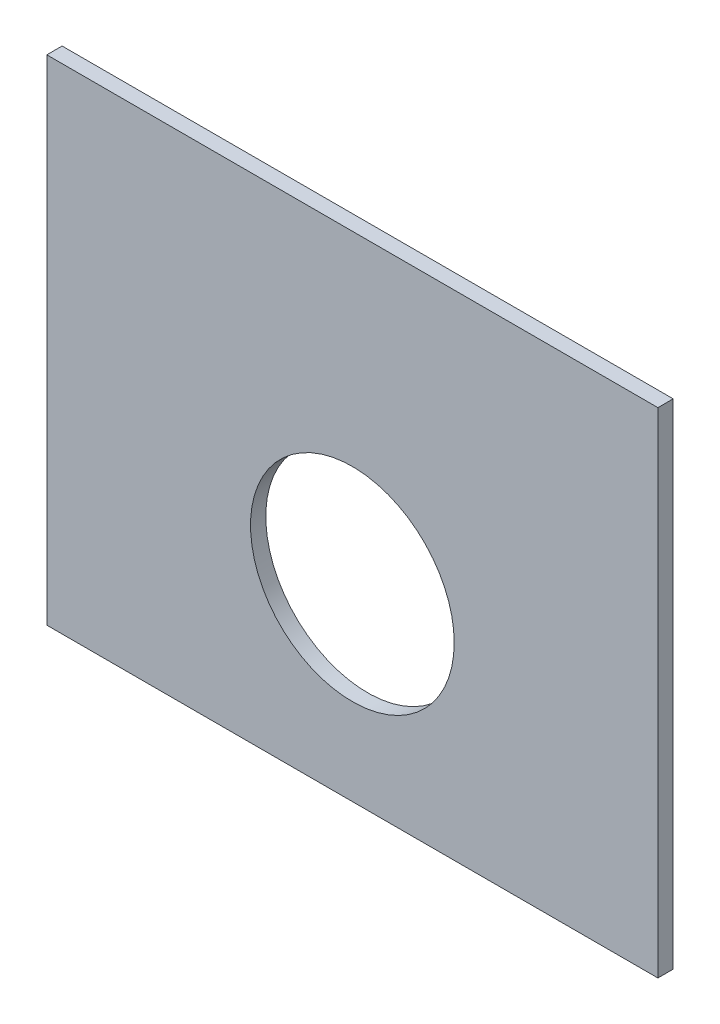
SolidWorks part; units mm, degrees
ref_plane "Plano frontal" through (0, 0, 0) normal (0, 0, 1) x (1, 0, 0)
ref_plane "Plano superior" through (0, 0, 0) normal (0, 1, 0) x (1, 0, 0)
ref_plane "Plano direito" through (0, 0, 0) normal (1, 0, 0) x (0, 0, -1)
sketch "Esboço1" plane through (0, 0, 0) normal (0, 0, 1) x (1, 0, 0)
  line L1 (60, -48.5) -> (-60, -48.5)
  line L2 (60, -48.5) -> (60, 48.5)
  line L3 (60, 48.5) -> (-60, 48.5)
  line L4 (-60, -48.5) -> (-60, 48.5)
  line L5 (60, -48.5) -> (-60, 48.5) construction
  line L6 (60, 48.5) -> (-60, -48.5) construction
  point P0 (0, 0)
  dimension "D1" = 120
  dimension "D2" = 97
extrude "Ressalto-extrusão1" add sketch "Esboço1" along normal blind 3
sketch "Esboço2" plane through (0, 0, 3) normal (0, 0, 1) x (1, 0, 0)
  line L0 (60, -48.5) -> (60, 48.5) construction
  line L1 (60, 48.5) -> (-60, 48.5) construction
  line L2 (-60, -48.5) -> (60, -48.5) construction
  circle A0 centre (0, -11.5) radius 20
  dimension "D1" = 40
  dimension "D2" = 60
  dimension "D3" = 60
extrude "Corte-extrusão1" cut sketch "Esboço2" against normal through all
